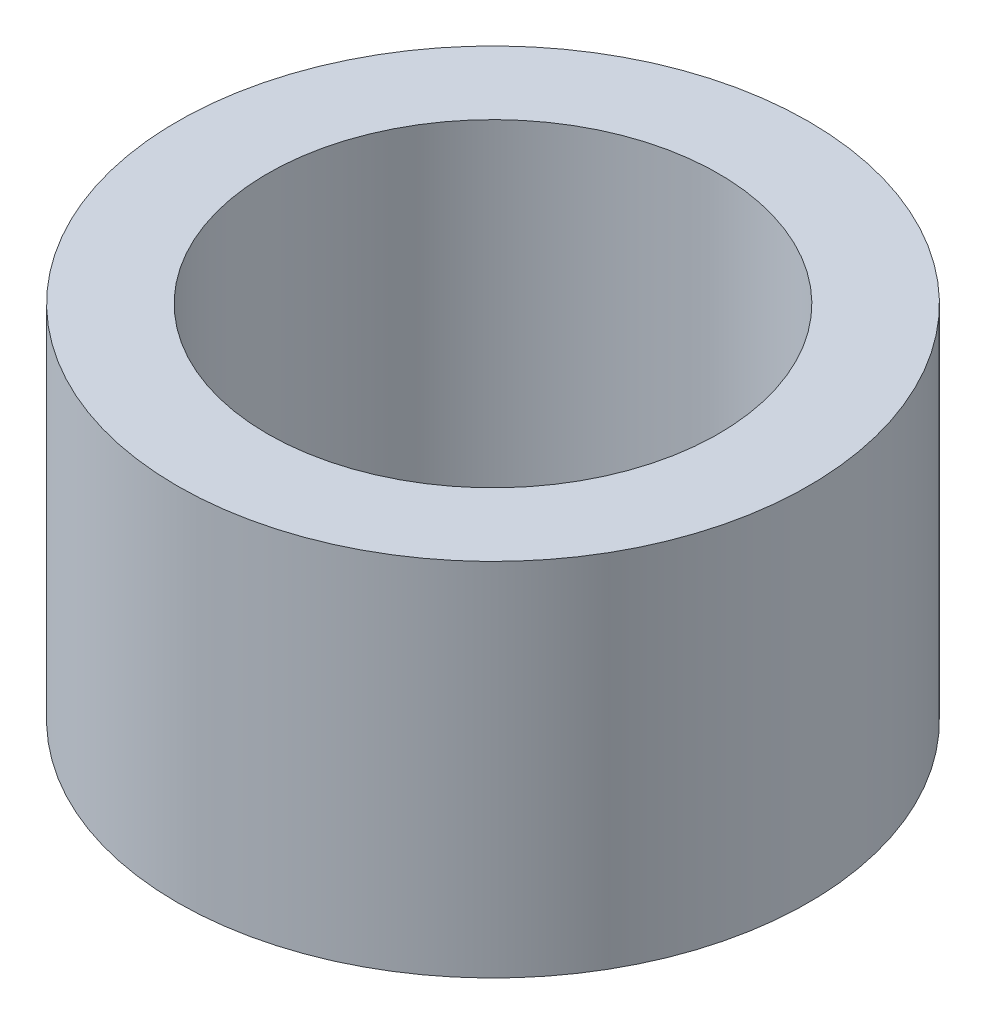
SolidWorks part; units mm, degrees
material "Bronzo per cuscinetti"
ref_plane "Piano frontale" through (0, 0, 0) normal (0, 0, 1) x (1, 0, 0)
ref_plane "Piano superiore" through (0, 0, 0) normal (0, 1, 0) x (1, 0, 0)
ref_plane "Piano destro" through (0, 0, 0) normal (1, 0, 0) x (0, 0, -1)
sketch "Schizzo1" plane through (0, 0, 0) normal (0, 1, 0) x (1, 0, 0)
  circle A0 centre (0, 0) radius 5
  circle A1 centre (0, 0) radius 7
  dimension "D1" = 10
  dimension "D2" = 14
extrude "Estrusione-Estrusione1" add sketch "Schizzo1" along normal blind 8
